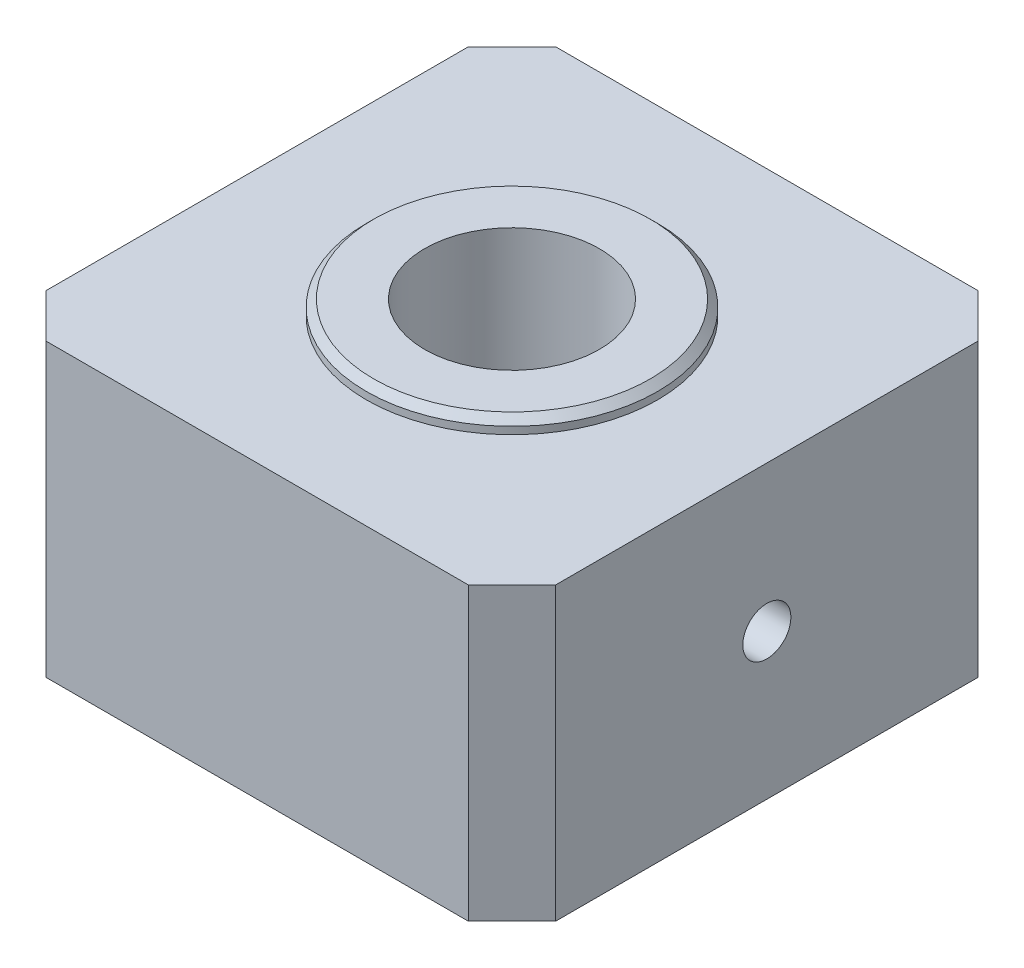
SolidWorks part; units mm, degrees
material "6061 Alloy"
ref_plane "Front Plane" through (0, 0, 0) normal (0, 0, 1) x (1, 0, 0)
ref_plane "Top Plane" through (0, 0, 0) normal (0, 1, 0) x (1, 0, 0)
ref_plane "Right Plane" through (0, 0, 0) normal (1, 0, 0) x (0, 0, -1)
sketch "Sketch1" plane through (0, 0, 0) normal (0, 1, 0) x (1, 0, 0)
  line L1 (17.5, -17.5) -> (-17.5, -17.5)
  line L2 (17.5, -17.5) -> (17.5, 17.5)
  line L3 (17.5, 17.5) -> (-17.5, 17.5)
  line L4 (-17.5, -17.5) -> (-17.5, 17.5)
  line L5 (17.5, -17.5) -> (-17.5, 17.5) construction
  line L6 (17.5, 17.5) -> (-17.5, -17.5) construction
  dimension "D2" = 35
  dimension "D3" = 35
extrude "Boss-Extrude1" add sketch "Sketch1" along normal blind 20
sketch "Sketch2" plane through (0, 20, 0) normal (0, 1, 0) x (1, 0, 0)
  circle A0 centre (0, 0) radius 10
  dimension "D1" = 20
extrude "Boss-Extrude2" add sketch "Sketch2" along normal blind 1
hole_wizard "M14 Tapped Hole1" positions "Sketch3" profile "Sketch4" tap size "M14" standard "GB"
sketch "Sketch3" plane through (0, 21, 0) normal (0, 1, 0) x (1, 0, 0)
  point P0 (0, 0)
cosmetic thread "Hole Thread1" parameters "D1"=8, "D2"=14
sketch "Sketch4" plane through (0, 21, 0) normal (1, 0, 0) x (0, 0, 1)
  line L0 (0, 0) -> (0, 17.6052)
  line L1 (0, 17.6052) -> (6, 14)
  line L2 (6, 14) -> (6, 0)
  line L5 (6, 0) -> (0, 0)
  line L10 (0, 17.6052) -> (-6, 14) construction
  line L11 (0, -6.35) -> (0, 107.95) construction
  dimension "Tap Drill Dia." = 12
  dimension "Tap Drill Depth" = 14
  dimension "Drill Angle" = 118
hole_wizard "M4 Tapped Hole1" positions "Sketch6" profile "Sketch7" tap size "M4" standard "GB"
sketch "Sketch6" plane through (0, 0, 0) normal (0, -1, 0) x (-1, 0, 0)
  line L0 (-11.55, 0) -> (11.55, 0) construction
  line L1 (0, 11.55) -> (0, -11.55) construction
  point P0 (-12.5, 12.5)
  point P5 (-12.5, -12.5)
  point P8 (12.5, -12.5)
  point P9 (12.5, 12.5)
  dimension "D1" = 25
  dimension "D2" = 25
sketch "Sketch7" plane through (12.5, 0, -12.5) normal (1, 0, 0) x (0, 0, -1)
  line L0 (0, 0) -> (0, 11.0914)
  line L1 (0, 11.0914) -> (1.65, 10.1)
  line L2 (1.65, 10.1) -> (1.65, 0)
  line L5 (1.65, 0) -> (0, 0)
  line L10 (0, 11.0914) -> (-1.65, 10.1) construction
  line L11 (0, -6.35) -> (0, 107.95) construction
  dimension "Tap Drill Dia." = 3.3
  dimension "Tap Drill Depth" = 10.1
  dimension "Drill Angle" = 118
cosmetic thread "Hole Thread2" parameters "D1"=8, "D2"=4
cosmetic thread "Hole Thread3" parameters "D1"=8, "D2"=4
cosmetic thread "Hole Thread4" parameters "D1"=8, "D2"=4
cosmetic thread "Hole Thread5" parameters "D1"=8, "D2"=4
hole_wizard "M4 Tapped Hole2" positions "Sketch8" profile "Sketch9" tap size "M4" standard "GB"
sketch "Sketch8" plane through (17.5, 0, 0) normal (1, 0, 0) x (0, 0, -1)
  line L0 (-17.5, 0) -> (17.5, 0) construction
  point P0 (0, 10)
  dimension "D1" = 10
sketch "Sketch9" plane through (17.5, 10, 0) normal (0, 1, 0) x (0, 0, -1)
  line L0 (0, 0) -> (0, 9.9914)
  line L1 (0, 9.9914) -> (1.65, 9)
  line L2 (1.65, 9) -> (1.65, 0)
  line L5 (1.65, 0) -> (0, 0)
  line L10 (0, 9.9914) -> (-1.65, 9) construction
  line L11 (0, -6.35) -> (0, 107.95) construction
  dimension "Tap Drill Dia." = 3.3
  dimension "Tap Drill Depth" = 9
  dimension "Drill Angle" = 118
cosmetic thread "Hole Thread6" parameters "D1"=8, "D2"=4
chamfer "Chamfer1" distance 3 angle 45 4 edges at (-17.5, 10, -17.5) (-17.5, 10, 17.5) (17.5, 10, 17.5) (17.5, 10, -17.5)
chamfer "Chamfer2" distance 0.5 angle 45 1 edges at (0, 21, 10)
